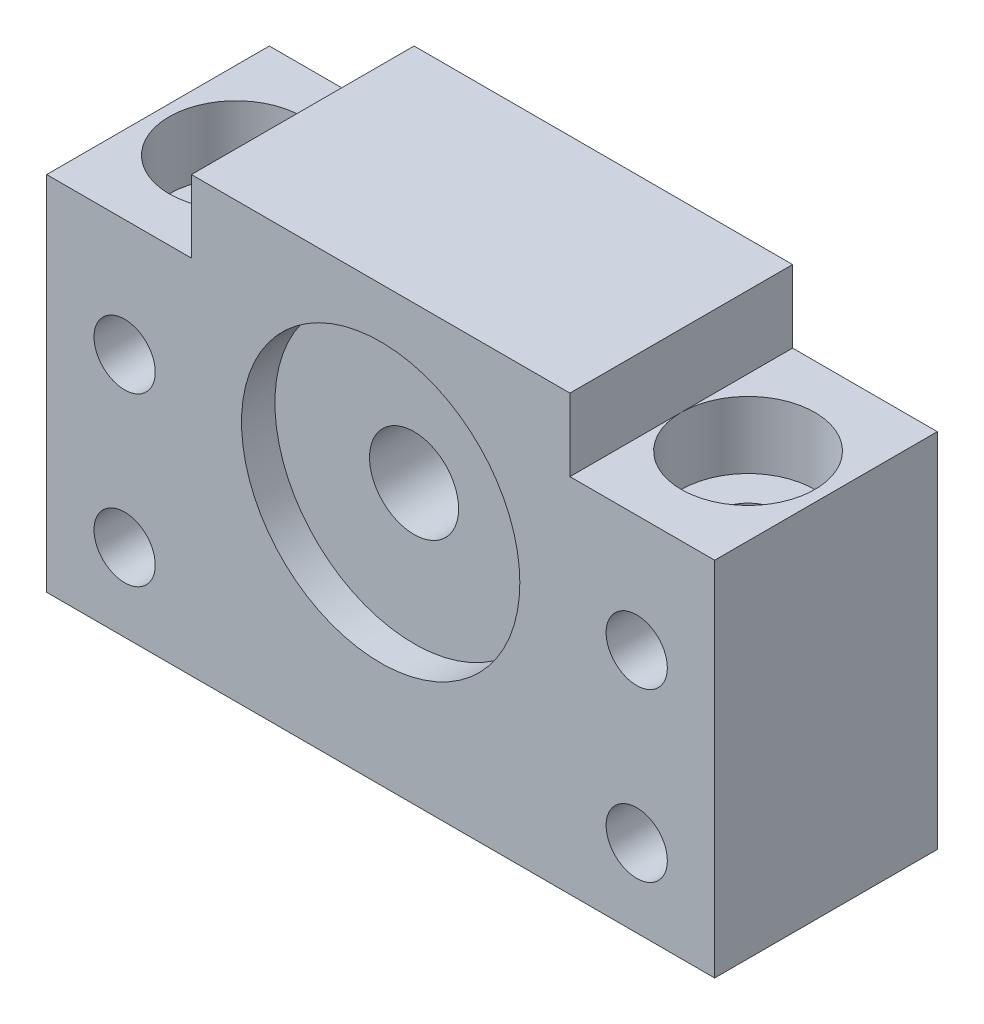
SolidWorks part; units mm, degrees
ref_plane "Спереди" through (0, 0, 0) normal (0, 0, 1) x (1, 0, 0)
ref_plane "Сверху" through (0, 0, 0) normal (0, 1, 0) x (1, 0, 0)
ref_plane "Справа" through (0, 0, 0) normal (1, 0, 0) x (0, 0, -1)
sketch "Эскиз1" plane through (0, 0, 0) normal (0, 0, 1) x (1, 0, 0)
  line L0 (47, 32.5) -> (60, 32.5)
  line L1 (0, 0) -> (60, 0)
  line L2 (0, 0) -> (0, 32.5)
  line L3 (0, 32.5) -> (13, 32.5)
  line L4 (60, 0) -> (60, 32.5)
  line L5 (30, 0) -> (30, 39) construction
  line L6 (13, 32.5) -> (13, 39)
  line L7 (13, 39) -> (47, 39)
  line L8 (47, 32.5) -> (47, 39)
  point P11 (18.2073, 36.7387)
  point P12 (20.7991, 31.8143)
  point P13 (0, 0)
  point P14 (26.7603, 23.3909)
  point P15 (30, 39)
  point P16 (30, 37.1274)
  dimension "D1" = 60
  dimension "D2" = 34
  dimension "D3" = 39
  dimension "D4" = 32.5
extrude "Бобышка-Вытянуть1" add sketch "Эскиз1" along normal blind 20
sketch "Эскиз2" plane through (0, 0, 20) normal (0, 0, 1) x (1, 0, 0)
  line L0 (0, 22) -> (60, 22) construction
  line L1 (0, 32.5) -> (0, 0) construction
  line L2 (60, 0) -> (60, 32.5) construction
  line L3 (30, 39) -> (30, 0) construction
  line L4 (47, 39) -> (13, 39) construction
  line L5 (0, 0) -> (60, 0) construction
  line L6 (53, 32.5) -> (53, 0.3871) construction
  line L7 (60, 32.5) -> (47, 32.5) construction
  line L8 (7, 32.5) -> (7, 0) construction
  line L9 (13, 32.5) -> (0, 32.5) construction
  line L10 (0, 7) -> (60, 7) construction
  circle A0 centre (7, 22) radius 2.75
  circle A1 centre (7, 7) radius 2.75
  circle A2 centre (53, 22) radius 2.75
  circle A3 centre (53, 7) radius 2.75
  circle A4 centre (30, 22) radius 4
  point P32 (49.1769, 22)
  point P33 (53, 22)
  point P34 (53, 22)
  dimension "D4" = 5.5
  dimension "D5" = 8
  dimension "D1" = 22
  dimension "D2" = 15
  dimension "D3" = 46
extrude "Вырез-Вытянуть1" cut sketch "Эскиз2" against normal through all
sketch "Эскиз3" plane through (0, 0, 20) normal (0, 0, 1) x (1, 0, 0)
  circle A0 centre (30, 22) radius 12.5
  dimension "D1" = 25
extrude "Вырез-Вытянуть2" cut sketch "Эскиз3" against normal blind 3
sketch "Эскиз4" plane through (0, 32.5, 0) normal (0, 1, 0) x (1, 0, 0)
  line L0 (0, -10) -> (60, -10) construction
  line L1 (0, -20) -> (0, 0) construction
  line L2 (60, -20) -> (60, 0) construction
  line L3 (50.25, -20) -> (55.75, -20) construction
  line L6 (4.25, -20) -> (9.75, -20) construction
  line L9 (50.25, -20) -> (55.75, -20) construction
  line L10 (4.25, -20) -> (9.75, -20) construction
  line L11 (7, -20) -> (7, 0) construction
  line L12 (13, 0) -> (0, 0) construction
  line L13 (53, -20) -> (53, 0) construction
  line L14 (60, 0) -> (47, 0) construction
  circle A0 centre (7, -10) radius 2.75
  circle A1 centre (53, -10) radius 2.75
  point P22 (53, -10)
  point P23 (54.8116, -10)
  point P24 (53, -10)
  point P25 (53, -10)
  point P26 (53, -10)
  point P27 (53, -10)
  point P28 (7, -10)
  dimension "D1" = 5.5
extrude "Вырез-Вытянуть3" cut sketch "Эскиз4" against normal through all
sketch "Эскиз5" plane through (0, 32.5, 0) normal (0, 1, 0) x (1, 0, 0)
  line L0 (13, -20) -> (13, 0) construction
  circle A0 centre (7, -10) radius 6
  circle A1 centre (53, -10) radius 6
extrude "Вырез-Вытянуть4" cut sketch "Эскиз5" against normal blind 6
